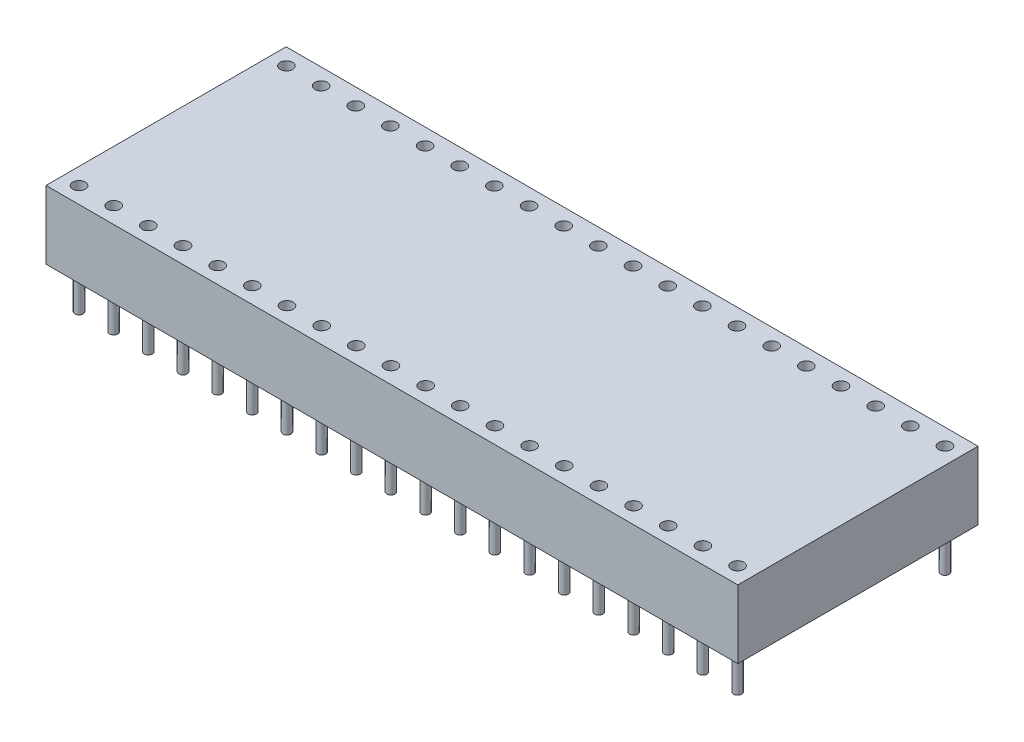
SolidWorks part; units mm, degrees
ref_plane "Спереди" through (0, 0, 0) normal (0, 0, 1) x (1, 0, 0)
ref_plane "Сверху" through (0, 0, 0) normal (0, 1, 0) x (1, 0, 0)
ref_plane "Справа" through (0, 0, 0) normal (1, 0, 0) x (0, 0, -1)
sketch "Эскиз1" plane through (0, 0, 0) normal (0, 1, 0) x (1, 0, 0)
  line L0 (-64.7461, 7.6) -> (55.073, 7.6) construction
  line L1 (-25.35, -8.8) -> (25.35, -8.8)
  line L2 (-25.35, -8.8) -> (-25.35, 8.8)
  line L3 (-25.35, 8.8) -> (25.35, 8.8)
  line L4 (25.35, -8.8) -> (25.35, 8.8)
  line L5 (-25.35, -8.8) -> (25.35, 8.8) construction
  line L6 (-25.35, 8.8) -> (25.35, -8.8) construction
  line L7 (-61.2568, 0) -> (63.1321, 0) construction
  circle A0 centre (-1.27, 7.6) radius 0.4575
  circle A1 centre (1.27, 7.6) radius 0.4575
  circle A2 centre (3.81, 7.6) radius 0.4575
  circle A3 centre (6.35, 7.6) radius 0.4575
  circle A4 centre (8.89, 7.6) radius 0.4575
  circle A5 centre (11.43, 7.6) radius 0.4575
  circle A6 centre (13.97, 7.6) radius 0.4575
  circle A7 centre (16.51, 7.6) radius 0.4575
  circle A8 centre (19.05, 7.6) radius 0.4575
  circle A9 centre (21.59, 7.6) radius 0.4575
  circle A10 centre (24.13, 7.6) radius 0.4575
  circle A31 centre (24.13, -7.6) radius 0.4575
  circle A32 centre (21.59, -7.6) radius 0.4575
  circle A33 centre (19.05, -7.6) radius 0.4575
  circle A34 centre (16.51, -7.6) radius 0.4575
  circle A35 centre (13.97, -7.6) radius 0.4575
  circle A36 centre (11.43, -7.6) radius 0.4575
  circle A37 centre (8.89, -7.6) radius 0.4575
  circle A38 centre (6.35, -7.6) radius 0.4575
  circle A39 centre (3.81, -7.6) radius 0.4575
  circle A40 centre (1.27, -7.6) radius 0.4575
  circle A41 centre (-1.27, -7.6) radius 0.4575
  circle A42 centre (-3.81, -7.6) radius 0.4575
  circle A43 centre (-3.81, 7.6) radius 0.4575
  circle A44 centre (-6.35, -7.6) radius 0.4575
  circle A45 centre (-6.35, 7.6) radius 0.4575
  circle A46 centre (-8.89, -7.6) radius 0.4575
  circle A47 centre (-8.89, 7.6) radius 0.4575
  circle A48 centre (-11.43, -7.6) radius 0.4575
  circle A49 centre (-11.43, 7.6) radius 0.4575
  circle A50 centre (-13.97, -7.6) radius 0.4575
  circle A51 centre (-13.97, 7.6) radius 0.4575
  circle A52 centre (-16.51, -7.6) radius 0.4575
  circle A53 centre (-16.51, 7.6) radius 0.4575
  circle A54 centre (-19.05, -7.6) radius 0.4575
  circle A55 centre (-19.05, 7.6) radius 0.4575
  circle A56 centre (-21.59, -7.6) radius 0.4575
  circle A57 centre (-21.59, 7.6) radius 0.4575
  circle A58 centre (-24.13, -7.6) radius 0.4575
  circle A59 centre (-24.13, 7.6) radius 0.4575
  circle A80 centre (-26.67, -7.6) radius 0.4575 [skipped]
  circle A81 centre (-26.67, 7.6) radius 0.4575 [skipped]
  circle A82 centre (-29.21, -7.6) radius 0.4575 [skipped]
  circle A83 centre (-29.21, 7.6) radius 0.4575 [skipped]
  circle A84 centre (-31.75, -7.6) radius 0.4575 [skipped]
  circle A85 centre (-31.75, 7.6) radius 0.4575 [skipped]
  circle A86 centre (-34.29, -7.6) radius 0.4575 [skipped]
  circle A87 centre (-34.29, 7.6) radius 0.4575 [skipped]
  circle A88 centre (-36.83, -7.6) radius 0.4575 [skipped]
  circle A89 centre (-36.83, 7.6) radius 0.4575 [skipped]
  circle A90 centre (-39.37, -7.6) radius 0.4575 [skipped]
  circle A91 centre (-39.37, 7.6) radius 0.4575 [skipped]
  circle A92 centre (-41.91, -7.6) radius 0.4575 [skipped]
  circle A93 centre (-41.91, 7.6) radius 0.4575 [skipped]
  circle A94 centre (-44.45, -7.6) radius 0.4575 [skipped]
  circle A95 centre (-44.45, 7.6) radius 0.4575 [skipped]
  circle A96 centre (-46.99, -7.6) radius 0.4575 [skipped]
  circle A97 centre (-46.99, 7.6) radius 0.4575 [skipped]
  circle A98 centre (-49.53, -7.6) radius 0.4575 [skipped]
  circle A99 centre (-49.53, 7.6) radius 0.4575 [skipped]
  point P0 (0, 0)
  dimension "D1" = 7.6
  dimension "D2" = 1.27
  dimension "D3" = 0.915
  dimension "D4" = 20
extrude "Бобышка-Вытянуть1" add sketch "Эскиз1" along normal blind 5
sketch "Эскиз2" plane through (0, 0, 0) normal (0, -1, 0) x (1, 0, 0)
  circle A0 centre (-24.13, 7.6) radius 0.3
  circle A1 centre (-21.59, 7.6) radius 0.3
  circle A2 centre (-19.05, 7.6) radius 0.3
  circle A3 centre (-16.51, 7.6) radius 0.3
  circle A4 centre (-13.97, 7.6) radius 0.3
  circle A5 centre (-11.43, 7.6) radius 0.3
  circle A6 centre (-8.89, 7.6) radius 0.3
  circle A7 centre (-6.35, 7.6) radius 0.3
  circle A8 centre (-3.81, 7.6) radius 0.3
  circle A9 centre (-1.27, 7.6) radius 0.3
  circle A10 centre (1.27, 7.6) radius 0.3
  circle A11 centre (3.81, 7.6) radius 0.3
  circle A12 centre (6.35, 7.6) radius 0.3
  circle A13 centre (8.89, 7.6) radius 0.3
  circle A14 centre (11.43, 7.6) radius 0.3
  circle A15 centre (13.97, 7.6) radius 0.3
  circle A16 centre (16.51, 7.6) radius 0.3
  circle A17 centre (19.05, 7.6) radius 0.3
  circle A18 centre (21.59, 7.6) radius 0.3
  circle A19 centre (24.13, 7.6) radius 0.3
  circle A20 centre (-21.59, -7.6) radius 0.3
  circle A21 centre (-19.05, -7.6) radius 0.3
  circle A22 centre (-16.51, -7.6) radius 0.3
  circle A23 centre (-13.97, -7.6) radius 0.3
  circle A24 centre (-11.43, -7.6) radius 0.3
  circle A25 centre (-8.89, -7.6) radius 0.3
  circle A26 centre (-6.35, -7.6) radius 0.3
  circle A27 centre (-3.81, -7.6) radius 0.3
  circle A28 centre (-1.27, -7.6) radius 0.3
  circle A29 centre (1.27, -7.6) radius 0.3
  circle A30 centre (3.81, -7.6) radius 0.3
  circle A31 centre (6.35, -7.6) radius 0.3
  circle A32 centre (8.89, -7.6) radius 0.3
  circle A33 centre (11.43, -7.6) radius 0.3
  circle A34 centre (13.97, -7.6) radius 0.3
  circle A35 centre (16.51, -7.6) radius 0.3
  circle A36 centre (19.05, -7.6) radius 0.3
  circle A37 centre (21.59, -7.6) radius 0.3
  circle A38 centre (24.13, -7.6) radius 0.3
  circle A39 centre (-24.13, -7.6) radius 0.3
  dimension "D1" = 20
  dimension "D2" = 2
extrude "Бобышка-Вытянуть2" add sketch "Эскиз2" along normal blind 3 separate body
